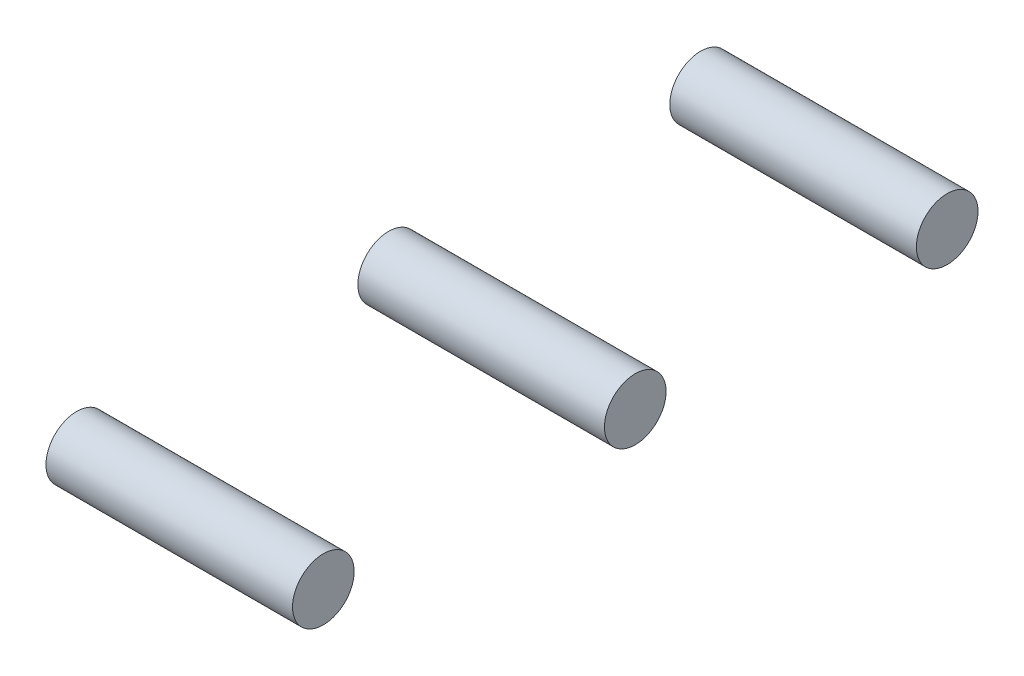
SolidWorks part; units mm, degrees
ref_plane "Front Plane" through (0, 0, 0) normal (0, 0, 1) x (1, 0, 0)
ref_plane "Top Plane" through (0, 0, 0) normal (0, 1, 0) x (1, 0, 0)
ref_plane "Right Plane" through (0, 0, 0) normal (1, 0, 0) x (0, 0, -1)
sketch "Sketch1" plane through (0, 0, 0) normal (1, 0, 0) x (0, 0, -1)
  line L0 (-25.3, 0) -> (25.3, 0) construction
  circle A0 centre (0, 0) radius 2.5
  circle A1 centre (-25.3, 0) radius 2.5
  circle A2 centre (25.3, 0) radius 2.5
  point P7 (0, 0)
  dimension "D1" = 5
  dimension "D2" = 25.3
extrude "Boss-Extrude1" add sketch "Sketch1" along normal blind 20
